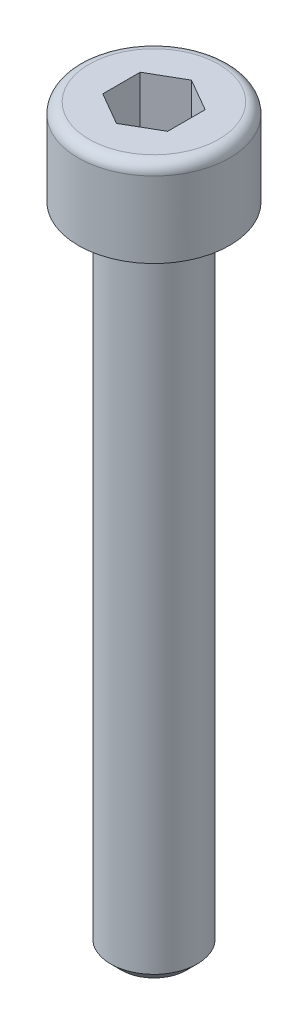
SolidWorks part; units mm, degrees
material "acero"
ref_plane "Alzado" through (0, 0, 0) normal (0, 0, 1) x (1, 0, 0)
ref_plane "Planta" through (0, 0, 0) normal (0, 1, 0) x (1, 0, 0)
ref_plane "Vista lateral" through (0, 0, 0) normal (1, 0, 0) x (0, 0, -1)
sketch "Croquis1" plane through (0, 0, 0) normal (0, 0, 1) x (1, 0, 0)
  line L0 (0, 0) -> (0, -60.9498) construction
  line L1 (0, 0) -> (3.5, 0)
  line L2 (3.5, 0) -> (3.5, -4)
  line L3 (3.5, -4) -> (2, -4)
  line L4 (2, -4) -> (2, -34)
  line L5 (2, -34) -> (0, -34)
  line L6 (0, -34) -> (0, 0)
  dimension "D1" = 30
  dimension "D2" = 4
  dimension "D3" = 7
  dimension "D4" = 4
revolve "Revolución1" add sketch "Croquis1" angle 360 about L0
sketch "Croquis2" plane through (0, 0, 0) normal (0, 1, 0) x (1, 0, 0)
  line L1 (1.5, 0.866) -> (0, 1.7321)
  line L2 (0, 1.7321) -> (-1.5, 0.866)
  line L3 (-1.5, 0.866) -> (-1.5, -0.866)
  line L4 (-1.5, -0.866) -> (0, -1.7321)
  line L5 (0, -1.7321) -> (1.5, -0.866)
  line L6 (1.5, -0.866) -> (1.5, 0.866)
  circle A0 centre (0, 0) radius 1.5 construction
  dimension "D1" = 3
extrude "Cortar-Extruir1" cut sketch "Croquis2" against normal blind 3
chamfer "Chaflán1" distance 0.5 angle 45 1 edges at (0, -34, 2)
fillet "Redondeo1" radius 0.5 1 edges at (0, 0, 3.5)
